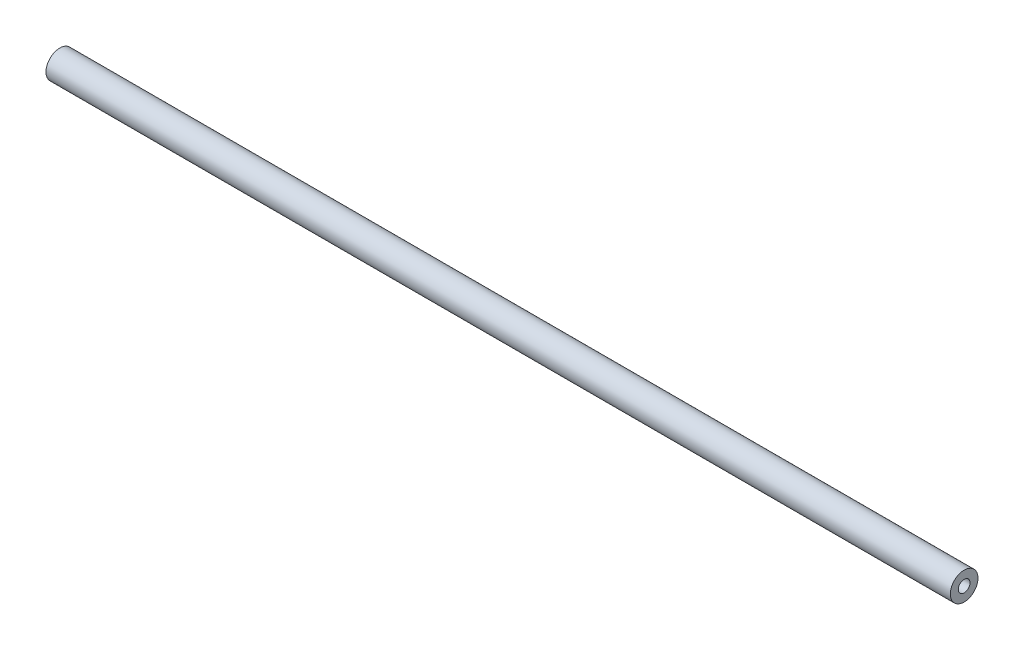
SolidWorks part; units mm, degrees
material "7075-T6 (SN)"
ref_plane "Front Plane" through (0, 0, 0) normal (0, 0, 1) x (1, 0, 0)
ref_plane "Top Plane" through (0, 0, 0) normal (0, 1, 0) x (1, 0, 0)
ref_plane "Right Plane" through (0, 0, 0) normal (1, 0, 0) x (0, 0, -1)
sketch "Sketch1" plane through (0, 0, 0) normal (1, 0, 0) x (0, 0, -1)
  circle A1 centre (0, 0) radius 4.7625
  dimension "D1" = 9.525
extrude "Boss-Extrude1" add sketch "Sketch1" along normal mid plane 311.15
hole_wizard "#10-32 Tapped Hole1" positions "3DSketch1" profile "Sketch2" tap size "#10-32" standard "ANSI Inch"
sketch3d "3DSketch1"
  line L0 (155.575, 0, 0) -> (-155.575, 0, 0) construction
  point P0 (155.575, 0, 0)
  point P7 (-155.575, 0, 0)
sketch "Sketch2" plane through (155.575, 0, 0) normal (0, 1, 0) x (0, 0, -1)
  line L0 (0, 0) -> (0, 13.2428)
  line L1 (0, 13.2428) -> (2.0193, 12.0294)
  line L2 (2.0193, 12.0294) -> (2.0193, 0)
  line L5 (2.0193, 0) -> (0, 0)
  line L10 (0, 13.2428) -> (-2.0193, 12.0294) construction
  line L11 (0, -6.35) -> (0, 107.95) construction
  dimension "Tap Drill Dia." = 4.0386
  dimension "Tap Drill Depth" = 12.0294
  dimension "Drill Angle" = 118
cosmetic thread "Hole Thread1"
cosmetic thread "Hole Thread2"
